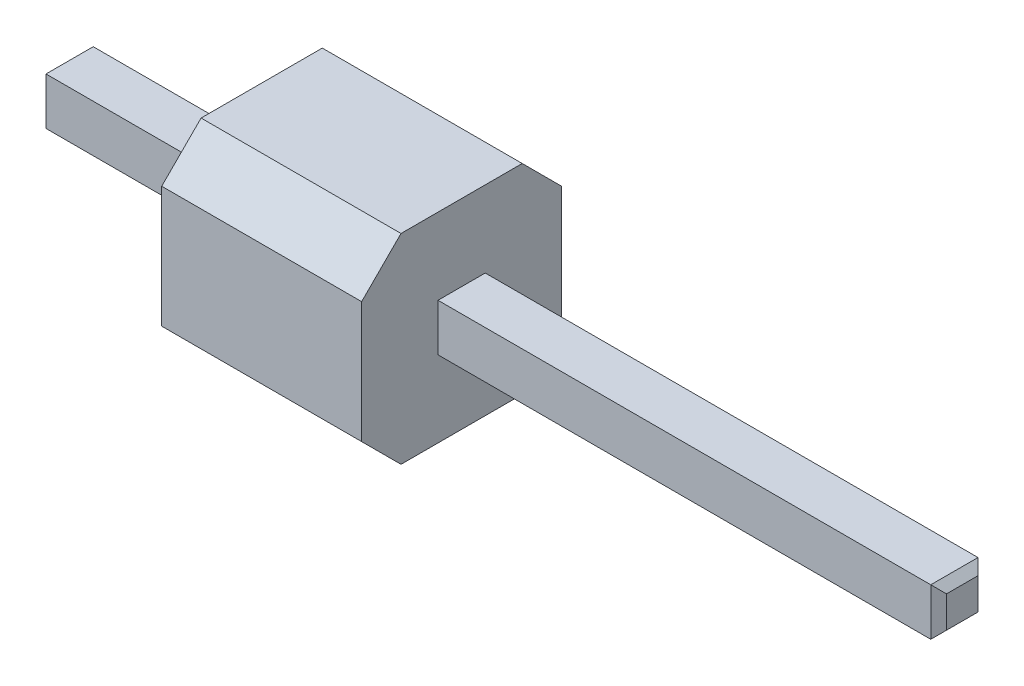
SolidWorks part; units mm, degrees
ref_plane "Front Plane" through (0, 0, 0) normal (0, 0, 1) x (1, 0, 0)
ref_plane "Top Plane" through (0, 0, 0) normal (0, 1, 0) x (1, 0, 0)
ref_plane "Right Plane" through (0, 0, 0) normal (1, 0, 0) x (0, 0, -1)
sketch "Sketch1" plane through (0, 0, 0) normal (1, 0, 0) x (0, 0, -1)
  line L0 (0, 0) -> (-1.27, 0) construction
  line L5 (-1.27, 0) -> (-1.27, 1.27) construction
  line L6 (-2.04, 1.27) -> (-0.5, 1.27)
  line L7 (-0.5, 1.27) -> (0, 0.77)
  line L8 (0, 0.77) -> (0, -0.77)
  line L9 (-2.54, 0.77) -> (-2.54, -0.77)
  line L10 (-2.04, 1.27) -> (-2.54, 0.77)
  line L11 (-0.5, -1.27) -> (0, -0.77)
  line L12 (-2.04, -1.27) -> (-0.5, -1.27)
  line L13 (-2.04, -1.27) -> (-2.54, -0.77)
  point P13 (-2.54, 0)
  dimension "D1" = 1.27
  dimension "D2" = 45
  dimension "D3" = 0.5
extrude "Plastic" add sketch "Sketch1" along normal blind 2.54
sketch "Sketch2" plane through (0, 0, 0) normal (0, 1, 0) x (1, 0, 0)
  line L0 (-2.54, -0.97) -> (-2.54, -1.57)
  line L1 (-2.54, -1.27) -> (8.9, -1.27) construction
  line L2 (0, -2.04) -> (0, -0.5) construction
  line L4 (-2.54, -1.57) -> (8.9, -1.57)
  line L6 (-2.54, -0.97) -> (8.9, -0.97)
  line L8 (8.9, -1.57) -> (8.9, -0.97)
  line L11 (-3.14, 3.36) -> (-3.14, -0.67) construction
  line L12 (-3.44, 3.36) -> (-3.44, -0.67) construction
  line L13 (-2.84, 3.36) -> (-2.84, -0.67) construction
  line L14 (2.54, -0.5) -> (2.54, -2.04) construction
  arc A3 (-3.44, -0.67) -> (-2.54, -1.57) centre (-2.54, -0.67) ccw construction
  arc A4 (-3.14, -0.67) -> (-2.54, -1.27) centre (-2.54, -0.67) ccw construction
  arc A5 (-2.84, -0.67) -> (-2.54, -0.97) centre (-2.54, -0.67) ccw construction
  point P5 (0, -1.27)
  dimension "D1" = 5.08
  dimension "D4" = 8.9
  dimension "D2" = 0.3
  dimension "D3" = 0.3
extrude "Contact" add sketch "Sketch2" along normal mid plane 0.6
chamfer "Chamfer1" distance 0.1 angle 45 8 edges at (8.9, 0.3, 1.27) (8.9, 0, 1.57) (8.9, -0.3, 1.27) (8.9, 0, 0.97) (-2.54, -0.3, 1.27) (-2.54, 0, 0.97) (-2.54, 0.3, 1.27) (-2.54, 0, 1.57)
